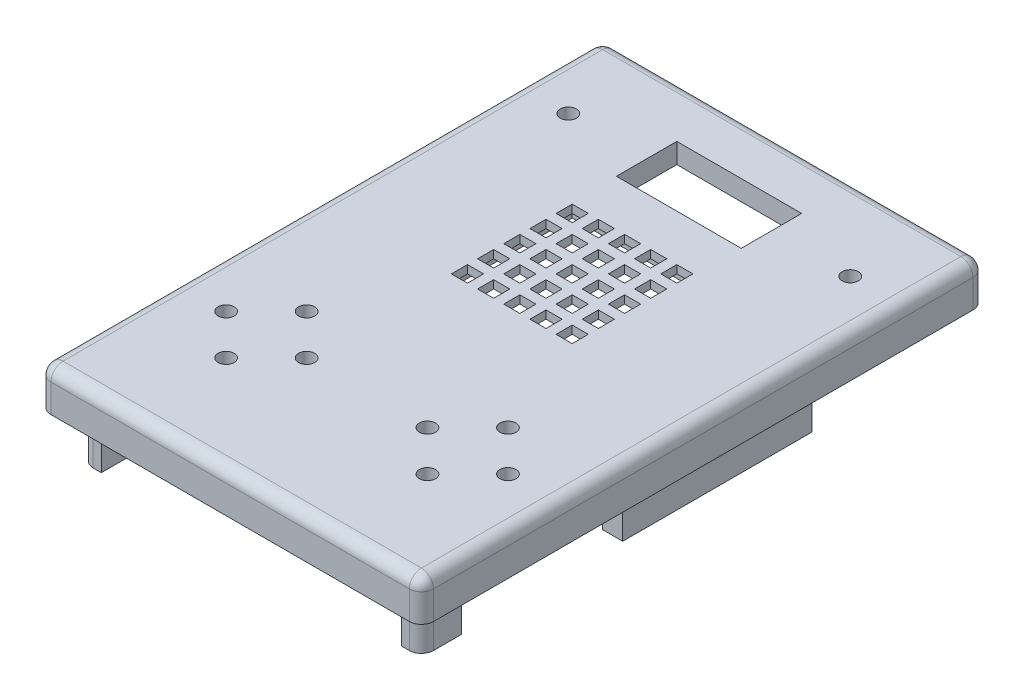
SolidWorks part; units mm, degrees
ref_plane "Front Plane" through (0, 0, 0) normal (0, 0, 1) x (1, 0, 0)
ref_plane "Top Plane" through (0, 0, 0) normal (0, 1, 0) x (1, 0, 0)
ref_plane "Right Plane" through (0, 0, 0) normal (1, 0, 0) x (0, 0, -1)
sketch "Sketch1" plane through (0, 0, 0) normal (0, 1, 0) x (1, 0, 0)
  line L1 (47.5, 70) -> (-47.5, 70)
  line L2 (47.5, 70) -> (47.5, -70)
  line L3 (47.5, -70) -> (-47.5, -70)
  line L4 (-47.5, 70) -> (-47.5, -70)
  line L5 (47.5, 70) -> (-47.5, -70) construction
  line L6 (47.5, -70) -> (-47.5, 70) construction
  point P0 (0, 0)
  dimension "D1" = 95
  dimension "D2" = 140
extrude "Boss-Extrude1" add sketch "Sketch1" along normal blind 10 contours L2 L1 L4 L3
sketch "Sketch7" plane through (0, 0, 0) normal (0, -1, 0) x (1, 0, 0)
  line L0 (0, 70) -> (0, -70) construction
  line L1 (-47.5, 70) -> (-42.25, 70) construction
  line L2 (-47.5, 70) -> (-47.5, 64.75) construction
  line L3 (-47.5, 64.75) -> (-42.25, 64.75) construction
  line L4 (-42.25, 70) -> (-42.25, 64.75) construction
  line L9 (-42.25, 64.75) -> (-37.25, 64.75)
  line L10 (-42.25, 64.75) -> (-42.25, -64.25)
  line L11 (-42.25, -64.25) -> (-37.25, -64.25)
  line L12 (-37.25, 64.75) -> (-37.25, -64.25)
  line L13 (47.5, 70) -> (-47.5, 70) construction
  line L14 (47.5, -70) -> (-47.5, -70) construction
  line L15 (42.25, -64.25) -> (37.25, -64.25)
  line L16 (37.25, 64.75) -> (37.25, -64.25)
  line L17 (42.25, 64.75) -> (37.25, 64.75)
  line L18 (42.25, 64.75) -> (42.25, -64.25)
  dimension "D1" = 5.25
  dimension "D2" = 5.25
  dimension "D3" = 5
  dimension "D4" = 129
extrude "Boss-Extrude3" add sketch "Sketch7" along normal blind 11.5
sketch "Sketch8" plane through (0, 10, 0) normal (0, 1, 0) x (1, 0, 0)
  line L1 (15.45, 56.48) -> (-15.55, 56.48)
  line L2 (15.45, 56.48) -> (15.45, 41.48)
  line L3 (15.45, 41.48) -> (-15.55, 41.48)
  line L4 (-15.55, 56.48) -> (-15.55, 41.48)
  line L5 (15.45, 56.48) -> (-15.55, 41.48) construction
  line L6 (15.45, 41.48) -> (-15.55, 56.48) construction
  line L8 (-14.1537, -37.3212) -> (14.2537, -37.3212) construction
  line L9 (0.05, -37.3212) -> (0.05, -46.9751) construction
  circle A0 centre (-35, 49) radius 2
  circle A2 centre (-35, 49) radius 1.5 construction
  circle A3 centre (35, 49) radius 2
  circle A4 centre (35, 49) radius 1.5 construction
  circle A5 centre (-14.95, -36.05) radius 1.5 construction
  circle A6 centre (15.05, -36.05) radius 1.5 construction
  circle A7 centre (-14.95, -36.05) radius 2
  circle A8 centre (-34.95, -36.05) radius 2
  circle A9 centre (-24.95, -46.05) radius 2
  circle A10 centre (-24.95, -26.05) radius 2
  circle A11 centre (-24.95, -26.05) radius 1.5 construction
  circle A12 centre (-34.95, -36.05) radius 1.5 construction
  circle A13 centre (-24.95, -46.05) radius 1.5 construction
  circle A14 centre (25.05, -26.05) radius 2
  circle A15 centre (35.05, -36.05) radius 2
  circle A16 centre (25.05, -46.05) radius 2
  circle A17 centre (15.05, -36.05) radius 2
  point P5 (-0.05, 48.98)
  dimension "D1" = 4
  dimension "D2" = 31
  dimension "D3" = 15
extrude "Cut-Extrude1" cut sketch "Sketch8" against normal blind 10
sketch "Sketch13" plane through (0, 10, 0) normal (0, 1, 0) x (1, 0, 0)
  line L4 (-13.045, 27.99) -> (-13.045, 1.99) construction
  line L5 (-13.045, 27.99) -> (12.955, 27.99) construction
  line L6 (12.955, 27.99) -> (12.955, 1.99) construction
  line L7 (12.955, 1.99) -> (-13.045, 1.99) construction
  line L8 (-13.045, 27.99) -> (-13.045, 41.48) construction
  line L9 (-15.55, 41.48) -> (15.45, 41.48) construction
  line L10 (-6.535, 27.99) -> (-6.545, 1.99) construction
  line L12 (-0.035, 27.99) -> (-0.035, 1.99) construction
  line L13 (6.465, 27.99) -> (6.455, 1.99) construction
  line L14 (-8.545, 29.99) -> (-8.545, 25.99)
  line L15 (-13.045, 21.49) -> (12.955, 21.49) construction
  line L16 (-13.045, 14.99) -> (12.955, 14.99) construction
  line L17 (-13.045, 8.49) -> (12.955, 8.49) construction
  line L18 (-8.545, 29.99) -> (-4.545, 29.99)
  line L19 (-4.545, 29.99) -> (-4.545, 25.99)
  line L20 (-15.045, 29.99) -> (-11.045, 29.99)
  line L21 (-15.045, 29.99) -> (-15.045, 25.99)
  line L22 (-15.045, 25.99) -> (-11.045, 25.99)
  line L23 (-11.045, 29.99) -> (-11.045, 25.99)
  line L24 (-15.045, 29.99) -> (-11.045, 25.99) construction
  line L25 (-15.045, 25.99) -> (-11.045, 29.99) construction
  line L26 (-8.545, 25.99) -> (-4.545, 25.99)
  line L27 (-2.045, 29.99) -> (-2.045, 25.99)
  line L28 (-2.045, 29.99) -> (1.955, 29.99)
  line L29 (1.955, 29.99) -> (1.955, 25.99)
  line L30 (-2.045, 25.99) -> (1.955, 25.99)
  line L31 (4.455, 29.99) -> (4.455, 25.99)
  line L32 (4.455, 29.99) -> (8.455, 29.99)
  line L33 (8.455, 29.99) -> (8.455, 25.99)
  line L34 (4.455, 25.99) -> (8.455, 25.99)
  line L35 (10.955, 29.99) -> (10.955, 25.99)
  line L36 (10.955, 29.99) -> (14.955, 29.99)
  line L37 (14.955, 29.99) -> (14.955, 25.99)
  line L38 (10.955, 25.99) -> (14.955, 25.99)
  line L39 (-8.545, 23.49) -> (-8.545, 19.49)
  line L40 (-8.545, 23.49) -> (-4.545, 23.49)
  line L41 (-4.545, 23.49) -> (-4.545, 19.49)
  line L42 (-8.545, 19.49) -> (-4.545, 19.49)
  line L43 (-2.045, 23.49) -> (-2.045, 19.49)
  line L44 (-2.045, 23.49) -> (1.955, 23.49)
  line L45 (1.955, 23.49) -> (1.955, 19.49)
  line L46 (-2.045, 19.49) -> (1.955, 19.49)
  line L47 (4.455, 23.49) -> (4.455, 19.49)
  line L48 (4.455, 23.49) -> (8.455, 23.49)
  line L49 (8.455, 23.49) -> (8.455, 19.49)
  line L50 (4.455, 19.49) -> (8.455, 19.49)
  line L51 (10.955, 23.49) -> (10.955, 19.49)
  line L52 (10.955, 23.49) -> (14.955, 23.49)
  line L53 (14.955, 23.49) -> (14.955, 19.49)
  line L54 (10.955, 19.49) -> (14.955, 19.49)
  line L55 (-8.545, 16.99) -> (-8.545, 12.99)
  line L56 (-8.545, 16.99) -> (-4.545, 16.99)
  line L57 (-4.545, 16.99) -> (-4.545, 12.99)
  line L58 (-8.545, 12.99) -> (-4.545, 12.99)
  line L59 (-2.045, 16.99) -> (-2.045, 12.99)
  line L60 (-2.045, 16.99) -> (1.955, 16.99)
  line L61 (1.955, 16.99) -> (1.955, 12.99)
  line L62 (-2.045, 12.99) -> (1.955, 12.99)
  line L63 (4.455, 16.99) -> (4.455, 12.99)
  line L64 (4.455, 16.99) -> (8.455, 16.99)
  line L65 (8.455, 16.99) -> (8.455, 12.99)
  line L66 (4.455, 12.99) -> (8.455, 12.99)
  line L67 (10.955, 16.99) -> (10.955, 12.99)
  line L68 (10.955, 16.99) -> (14.955, 16.99)
  line L69 (14.955, 16.99) -> (14.955, 12.99)
  line L70 (10.955, 12.99) -> (14.955, 12.99)
  line L71 (-8.545, 10.49) -> (-8.545, 6.49)
  line L72 (-8.545, 10.49) -> (-4.545, 10.49)
  line L73 (-4.545, 10.49) -> (-4.545, 6.49)
  line L74 (-8.545, 6.49) -> (-4.545, 6.49)
  line L75 (-2.045, 10.49) -> (-2.045, 6.49)
  line L76 (-2.045, 10.49) -> (1.955, 10.49)
  line L77 (1.955, 10.49) -> (1.955, 6.49)
  line L78 (-2.045, 6.49) -> (1.955, 6.49)
  line L79 (4.455, 10.49) -> (4.455, 6.49)
  line L80 (4.455, 10.49) -> (8.455, 10.49)
  line L81 (8.455, 10.49) -> (8.455, 6.49)
  line L82 (4.455, 6.49) -> (8.455, 6.49)
  line L83 (10.955, 10.49) -> (10.955, 6.49)
  line L84 (10.955, 10.49) -> (14.955, 10.49)
  line L85 (14.955, 10.49) -> (14.955, 6.49)
  line L86 (10.955, 6.49) -> (14.955, 6.49)
  line L87 (-8.545, 3.99) -> (-8.545, -0.01)
  line L88 (-8.545, 3.99) -> (-4.545, 3.99)
  line L89 (-4.545, 3.99) -> (-4.545, -0.01)
  line L90 (-8.545, -0.01) -> (-4.545, -0.01)
  line L91 (-2.045, 3.99) -> (-2.045, -0.01)
  line L92 (-2.045, 3.99) -> (1.955, 3.99)
  line L93 (1.955, 3.99) -> (1.955, -0.01)
  line L94 (-2.045, -0.01) -> (1.955, -0.01)
  line L95 (4.455, 3.99) -> (4.455, -0.01)
  line L96 (4.455, 3.99) -> (8.455, 3.99)
  line L97 (8.455, 3.99) -> (8.455, -0.01)
  line L98 (4.455, -0.01) -> (8.455, -0.01)
  line L99 (10.955, 3.99) -> (10.955, -0.01)
  line L100 (10.955, 3.99) -> (14.955, 3.99)
  line L101 (14.955, 3.99) -> (14.955, -0.01)
  line L102 (10.955, -0.01) -> (14.955, -0.01)
  line L103 (-15.045, 23.49) -> (-15.045, 19.49)
  line L104 (-15.045, 23.49) -> (-11.045, 23.49)
  line L105 (-11.045, 23.49) -> (-11.045, 19.49)
  line L106 (-15.045, 19.49) -> (-11.045, 19.49)
  line L107 (-15.045, 16.99) -> (-15.045, 12.99)
  line L108 (-15.045, 16.99) -> (-11.045, 16.99)
  line L109 (-11.045, 16.99) -> (-11.045, 12.99)
  line L110 (-15.045, 12.99) -> (-11.045, 12.99)
  line L111 (-15.045, 10.49) -> (-15.045, 6.49)
  line L112 (-15.045, 10.49) -> (-11.045, 10.49)
  line L113 (-11.045, 10.49) -> (-11.045, 6.49)
  line L114 (-15.045, 6.49) -> (-11.045, 6.49)
  line L115 (-15.045, 3.99) -> (-15.045, -0.01)
  line L116 (-15.045, 3.99) -> (-11.045, 3.99)
  line L117 (-11.045, 3.99) -> (-11.045, -0.01)
  line L118 (-15.045, -0.01) -> (-11.045, -0.01)
  dimension "D1" = 26
  dimension "D2" = 4
  dimension "D3" = 5
  dimension "D4" = 5
sketch "Sketch14" plane through (0, 0, 0) normal (0, -1, 0) x (1, 0, 0)
  line L1 (-17.045, 2.01) -> (16.955, 2.01)
  line L2 (-17.045, 2.01) -> (-17.045, -31.99)
  line L3 (-17.045, -31.99) -> (16.955, -31.99)
  line L4 (16.955, 2.01) -> (16.955, -31.99)
extrude "Cut-Extrude3" cut sketch "Sketch14" against normal blind 8
extrude "Cut-Extrude4" cut sketch "Sketch13" against normal blind 7
sketch "Sketch15" plane through (0, 0, 0) normal (0, -1, 0) x (1, 0, 0)
  line L1 (-37.25, 64.75) -> (37.25, 64.75)
  line L2 (-37.25, 64.75) -> (-37.25, -64.25)
  line L3 (-37.25, -64.25) -> (37.25, -64.25)
  line L4 (37.25, 64.75) -> (37.25, -64.25)
extrude "Cut-Extrude5" cut sketch "Sketch15" against normal blind 5
sketch "Sketch18" plane through (0, -11.5, 0) normal (0, -1, 0) x (1, 0, 0)
  line L0 (-37.25, -64.25) -> (-37.25, 64.75) construction
  line L1 (-42.25, -64.25) -> (-37.25, -64.25)
  line L2 (-42.25, -64.25) -> (-42.25, -32.25)
  line L3 (-42.25, -32.25) -> (-37.25, -32.25)
  line L4 (-37.25, -64.25) -> (-37.25, -32.25)
  line L5 (-42.25, 64.75) -> (-42.25, 54.75) construction
  line L6 (-42.25, 64.75) -> (-42.25, -64.25) construction
  line L7 (-47.5, 70) -> (0, 70) construction
  line L8 (-42.25, 54.75) -> (-37.25, 54.75)
  line L9 (-42.25, 54.75) -> (-42.25, 14.75)
  line L10 (-42.25, 14.75) -> (-37.25, 14.75)
  line L11 (-37.25, 54.75) -> (-37.25, 14.75)
  line L12 (47.5, 70) -> (-47.5, 70) construction
  line L13 (0, 70) -> (0, -70) construction
  line L14 (47.5, -70) -> (-47.5, -70) construction
  line L15 (42.25, -32.25) -> (37.25, -32.25)
  line L16 (37.25, -64.25) -> (37.25, -32.25)
  line L17 (42.25, -64.25) -> (37.25, -64.25)
  line L18 (42.25, -64.25) -> (42.25, -32.25)
  line L19 (42.25, 14.75) -> (37.25, 14.75)
  line L20 (37.25, 54.75) -> (37.25, 14.75)
  line L21 (42.25, 54.75) -> (37.25, 54.75)
  line L22 (42.25, 54.75) -> (42.25, 14.75)
  dimension "D1" = 32
  dimension "D2" = 10
  dimension "D3" = 40
extrude "Cut-Extrude8" cut sketch "Sketch18" against normal up to surface (16.5 mm away) up to face at (35, 5, -51)
fillet "Fillet1" radius 3 12 edges at (-42.25, 2.5, -64.25) (42.25, 2.5, -64.25) (-42.25, -5.75, 64.75) (42.25, -5.75, 64.75) (47.5, 5, 70) (-47.5, 5, 70) (0, 10, 70) (47.5, 5, -70) (-47.5, 5, -70) (-47.5, 10, 0) (47.5, 10, 0) (0, 10, -70)
